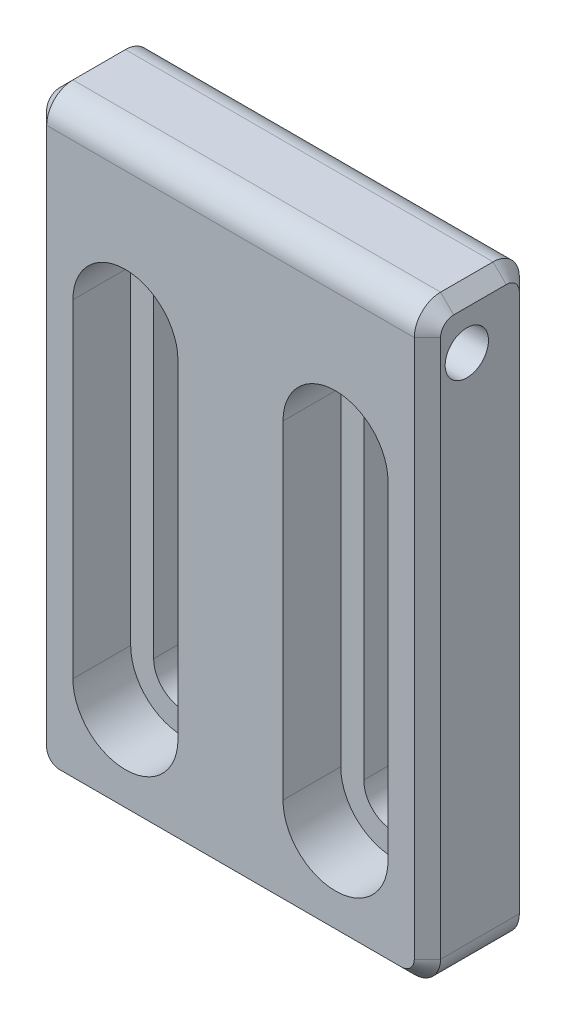
SolidWorks part; units mm, degrees
material "Alumina"
ref_plane "Front Plane" through (0, 0, 0) normal (0, 0, 1) x (1, 0, 0)
ref_plane "Top Plane" through (0, 0, 0) normal (0, 1, 0) x (1, 0, 0)
ref_plane "Right Plane" through (0, 0, 0) normal (1, 0, 0) x (0, 0, -1)
sketch "Sketch1" plane through (0, 0, 0) normal (0, 0, 1) x (1, 0, 0)
  line L1 (-15, 37.5) -> (15, 37.5)
  line L2 (-15, 37.5) -> (-15, -37.5)
  line L3 (-15, -37.5) -> (15, -37.5)
  line L4 (15, 37.5) -> (15, -37.5)
  line L5 (-15, 37.5) -> (15, -37.5) construction
  line L6 (-15, -37.5) -> (15, 37.5) construction
  point P0 (0, 0)
  dimension "D1" = 30
  dimension "D2" = 75
extrude "Boss-Extrude1" add sketch "Sketch1" along normal blind 8
hole_wizard "M4 Tapped Hole1" positions "Sketch2" profile "Sketch3" tap size "M4" standard "DIN"
sketch "Sketch2" plane through (15, 0, 0) normal (1, 0, 0) x (0, 0, -1)
  line L0 (-8, 37.5) -> (0, 37.5) construction
  line L1 (-8, -37.5) -> (-8, 37.5) construction
  point P0 (-5, 33.5)
  dimension "D1" = 4
  dimension "D2" = 3
sketch "Sketch3" plane through (15, 33.5, 5) normal (0, 1, 0) x (0, 0, -1)
  line L0 (0, 0) -> (0, 12.4914)
  line L1 (0, 12.4914) -> (1.65, 11.5)
  line L2 (1.65, 11.5) -> (1.65, 0)
  line L5 (1.65, 0) -> (0, 0)
  line L10 (0, 12.4914) -> (-1.65, 11.5) construction
  line L11 (0, -6.35) -> (0, 107.95) construction
  dimension "Tap Drill Dia." = 3.3
  dimension "Tap Drill Depth" = 11.5
  dimension "Drill Angle" = 118
cosmetic thread "Hole Thread1" parameters "D1"=8, "D2"=4
fillet "Fillet2" radius 2 2 edges at (0, 37.5, 0) (0, 37.5, 8)
sketch "Sketch7" plane through (0, 0, 0) normal (0, 0, -1) x (-1, 0, 0)
  line L0 (-8, 20) -> (-8, 0) construction
  line L1 (-4, 20) -> (-4, 0)
  line L2 (-12, 20) -> (-12, 0)
  line L3 (0, 5.6643) -> (0, 20) construction
  line L4 (8, 20) -> (8, 0) construction
  line L5 (4, 20) -> (4, 0)
  line L6 (12, 20) -> (12, 0)
  arc A0 (-4, 20) -> (-12, 20) centre (-8, 20) ccw
  arc A1 (-12, 0) -> (-4, 0) centre (-8, 0) ccw
  arc A2 (4, 20) -> (12, 20) centre (8, 20) cw
  arc A3 (12, 0) -> (4, 0) centre (8, 0) cw
  point P2 (-8, 10)
  point P12 (8, 10)
  dimension "D1" = 8
sketch "Sketch9" plane through (0, 0, 8) normal (0, 0, 1) x (1, 0, 0)
  line L0 (-8, 0) -> (-8, 25) construction
  line L1 (-12, 0) -> (-12, 25)
  line L2 (-4, 0) -> (-4, 25)
  line L3 (0, 0) -> (0, 28.9294) construction
  line L4 (8, 0) -> (8, 25) construction
  line L5 (12, 0) -> (12, 25)
  line L6 (4, 0) -> (4, 25)
  arc A0 (-12, 0) -> (-4, 0) centre (-8, 0) ccw
  arc A1 (-4, 25) -> (-12, 25) centre (-8, 25) ccw
  arc A2 (12, 0) -> (4, 0) centre (8, 0) cw
  arc A3 (4, 25) -> (12, 25) centre (8, 25) cw
  point P2 (-8, 12.5)
  point P12 (8, 12.5)
  dimension "D1" = 8
extrude "Cut-Extrude3" cut sketch "Sketch9" against normal blind 4.4
sketch "Sketch10" plane through (0, 0, 3.6) normal (0, 0, 1) x (1, 0, 0)
  line L0 (-8, 25) -> (-8, 0) construction
  line L1 (-5.75, 25) -> (-5.75, 0)
  line L2 (-10.25, 25) -> (-10.25, 0)
  line L3 (0, 14.9331) -> (0, 24.4109) construction
  line L4 (8, 25) -> (8, 0) construction
  line L5 (5.75, 25) -> (5.75, 0)
  line L6 (10.25, 25) -> (10.25, 0)
  arc A0 (-5.75, 25) -> (-10.25, 25) centre (-8, 25) ccw
  arc A1 (-10.25, 0) -> (-5.75, 0) centre (-8, 0) ccw
  arc A2 (5.75, 25) -> (10.25, 25) centre (8, 25) cw
  arc A3 (10.25, 0) -> (5.75, 0) centre (8, 0) cw
  point P4 (-8, 12.5)
  point P14 (8, 12.5)
extrude "Cut-Extrude4" cut sketch "Sketch10" against normal blind 4.4
sketch "Sketch11" plane through (0, 0, 8) normal (0, 0, 1) x (1, 0, 0)
  line L0 (-15, 35.5) -> (-15, -37.5) construction
  line L1 (15, -37.5) -> (-15, -37.5)
  line L2 (15, -37.5) -> (15, -7.5)
  line L3 (15, -7.5) -> (-15, -7.5)
  line L4 (-15, -37.5) -> (-15, -7.5)
  dimension "D1" = 30
extrude "Cut-Extrude5" cut sketch "Sketch11" against normal blind 29.4
fillet "Fillet3" radius 2 2 edges at (15, -7.5, 4) (-15, -7.5, 4)
ref_plane "Plane1" through (0, 0, 0) normal (1, 0, 0) x (0, 0, -1)
mirror "Mirror1" about plane through (0, 0, 0) normal (1, 0, 0) of "M4 Tapped Hole1"
chamfer "Chamfer1" distance 1 angle 45 16 edges at (-15, 15, 8) (-15, 36.9142, 7.4142) (-14.4142, -6.9142, 8) (-15, 37.5, 4) (0, -7.5, 8) (-15, 36.9142, 0.5858) (14.4142, -6.9142, 8) (-15, 15, 0) (15, 15, 8) (-14.4142, -6.9142, 0) (15, 36.9142, 7.4142) (0, -7.5, 0) (15, 37.5, 4) (14.4142, -6.9142, 0) (15, 36.9142, 0.5858) (15, 15, 0)
